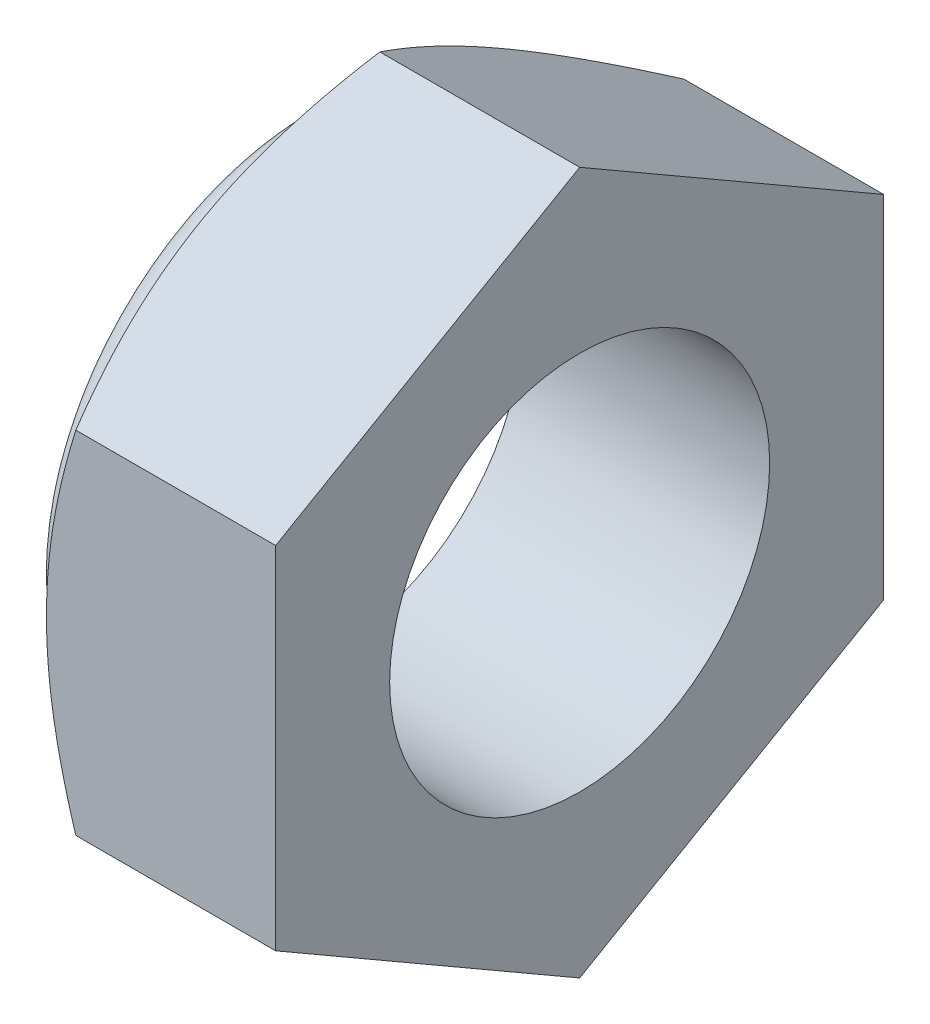
SolidWorks part; units mm, degrees
ref_plane "Front Plane" through (0, 0, 0) normal (0, 0, 1) x (1, 0, 0)
ref_plane "Top Plane" through (0, 0, 0) normal (0, 1, 0) x (1, 0, 0)
ref_plane "Right Plane" through (0, 0, 0) normal (1, 0, 0) x (0, 0, -1)
sketch "Sketch1" plane through (0, 0, 0) normal (1, 0, 0) x (0, 0, -1)
  line L0 (-16, 9.2376) -> (-16, -9.2376)
  line L1 (-16, -9.2376) -> (0, -18.4752)
  line L2 (0, -18.4752) -> (16, -9.2376)
  line L3 (16, -9.2376) -> (16, 9.2376)
  line L4 (16, 9.2376) -> (0, 18.4752)
  line L5 (0, 18.4752) -> (-16, 9.2376)
  circle A0 centre (0, 0) radius 18.4752 construction
  circle A1 centre (0, 0) radius 10
  dimension "D2" = 20
  dimension "D1" = 32
extrude "Boss-Extrude1" add sketch "Sketch1" along normal blind 13
sketch "Sketch2" plane through (0, 0, 0) normal (0, 1, 0) x (1, 0, 0)
  line L0 (0, 14.5) -> (3.1376, 19.5212)
  line L1 (0, 16) -> (0, 0) construction
  line L2 (3.1376, 19.5212) -> (-1.1528, 19.5212)
  line L3 (-1.1528, 19.5212) -> (-1.1528, 14.5)
  line L4 (-1.1528, 14.5) -> (0, 14.5)
  line L5 (0, 0) -> (16.8991, 0) construction
  dimension "D1" = 14.5
revolve "Cut-Revolve1" cut sketch "Sketch2" angle 360 about L5
sketch "Sketch4" plane through (0, 0, 0) normal (0, 1, 0) x (1, 0, 0)
  line L0 (0, 14.5) -> (0, -14.5) construction
  line L1 (0, 11.75) -> (0, 14.5)
  line L2 (0, 0) -> (17.3672, 0) construction
  arc A0 (0, 14.5) -> (0, 11.75) centre (0, 13.125) ccw
  dimension "D1" = 11.75
revolve "Revolve1" add sketch "Sketch4" angle 360 about L2
